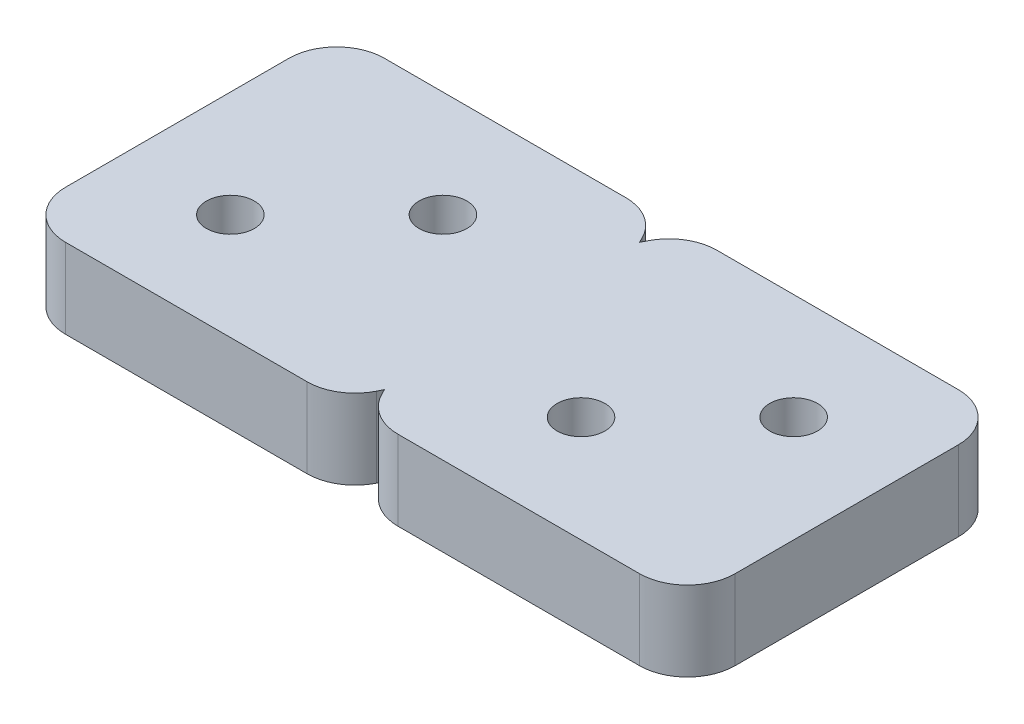
SolidWorks part; units mm, degrees
ref_plane "Front Plane" through (0, 0, 0) normal (0, 0, 1) x (1, 0, 0)
ref_plane "Top Plane" through (0, 0, 0) normal (0, 1, 0) x (1, 0, 0)
ref_plane "Right Plane" through (0, 0, 0) normal (1, 0, 0) x (0, 0, -1)
sketch "Sketch1" plane through (0, 0, 0) normal (0, 1, 0) x (1, 0, 0)
  line L0 (-51.1642, -4.2311) -> (-51.1642, -29.6311)
  line L1 (-51.1642, -29.6311) -> (-25.7642, -29.6311)
  line L2 (2.1758, -29.6311) -> (2.1758, -4.2311)
  line L3 (2.1758, -4.2311) -> (-23.2242, -4.2311)
  line L4 (-24.4942, -6.7711) -> (-25.7642, -4.2311)
  line L5 (-24.4942, -6.7711) -> (-23.2242, -4.2311)
  line L6 (-25.7642, -4.2311) -> (-51.1642, -4.2311)
  line L7 (-51.1642, -16.9311) -> (2.1758, -16.9311) construction
  line L8 (-24.4942, -27.0911) -> (-25.7642, -29.6311)
  line L9 (-24.4942, -27.0911) -> (-23.2242, -29.6311)
  line L10 (-23.2242, -29.6311) -> (2.1758, -29.6311)
  circle A7 centre (-42.6988, -21.1657) radius 1.905
  circle A8 centre (-34.2296, -12.6965) radius 1.905
  circle A9 centre (-14.7588, -21.1657) radius 1.905
  circle A10 centre (-6.2896, -12.6965) radius 1.905
extrude "Boss-Extrude1" add sketch "Sketch1" along normal blind 6.35
fillet "Fillet1" radius 3.81 8 edges at (-51.1642, 3.175, 4.2311) (-23.2242, 3.175, 4.2311) (-25.7642, 3.175, 4.2311) (2.1758, 3.175, 4.2311) (2.1758, 3.175, 29.6311) (-23.2242, 3.175, 29.6311) (-25.7642, 3.175, 29.6311) (-51.1642, 3.175, 29.6311)
